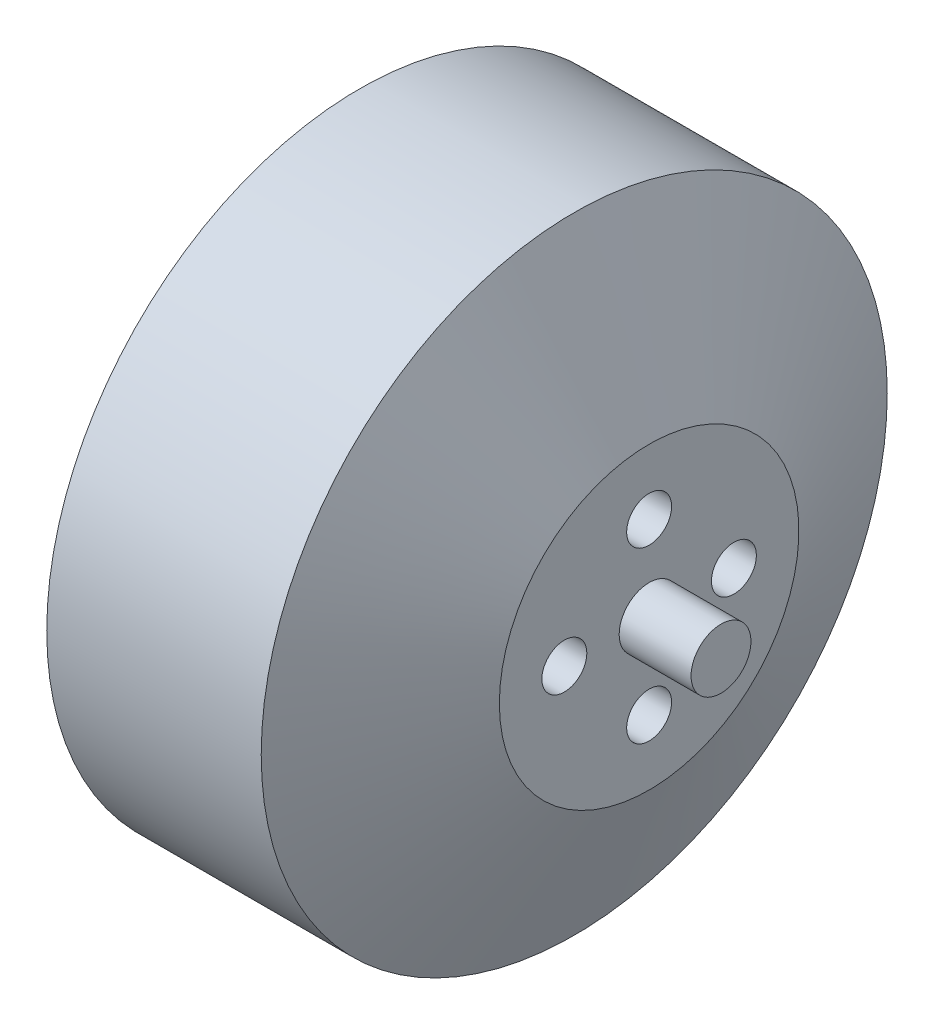
SolidWorks part; units mm, degrees
ref_plane "Plan de face" through (0, 0, 0) normal (0, 0, 1) x (1, 0, 0)
ref_plane "Plan de dessus" through (0, 0, 0) normal (0, 1, 0) x (1, 0, 0)
ref_plane "Plan de droite" through (0, 0, 0) normal (1, 0, 0) x (0, 0, -1)
sketch "Esquisse1" plane through (0, 0, 0) normal (0, 0, 1) x (1, 0, 0)
  line L0 (0, 0) -> (31.3198, 0) construction
  line L1 (0, 20.9) -> (14.32, 20.9)
  line L2 (14.32, 20.9) -> (19.32, 10)
  line L3 (19.32, 10) -> (19.32, 2)
  line L4 (19.32, 2) -> (24.12, 2)
  line L5 (24.12, 2) -> (24.12, 0)
  line L6 (24.12, 0) -> (0, 0)
  line L7 (0, 0) -> (0, 20.9)
  dimension "D1" = 2
  dimension "D2" = 10
  dimension "D3" = 14.32
  dimension "D4" = 5
  dimension "D5" = 20.9
  dimension "D6" = 4.8
revolve "Révolution1" add sketch "Esquisse1" angle 360 about L0
sketch "Esquisse2" plane through (19.32, 0, 0) normal (1, 0, 0) x (0, 0, -1)
  line L0 (-5.66, 0) -> (5.66, 0) construction
  line L1 (0, 0) -> (5.421, 5.421) construction
  line L2 (0, -5.66) -> (0, 5.66) construction
  circle A0 centre (0, -5.66) radius 1.5
  circle A1 centre (-5.66, 0) radius 1.5
  circle A2 centre (0, 5.66) radius 1.5
  circle A3 centre (5.66, 0) radius 1.5
  circle A4 centre (0, 0) radius 10 construction
  dimension "D1" = 3
  dimension "D2" = 3
  dimension "D3" = 20
  dimension "D4" = 11.32
  dimension "D5" = 45
extrude "Enlèv. mat.-Extru.1" cut sketch "Esquisse2" against normal blind 7.5
sketch "Esquisse3" plane through (0, 0, 0) normal (-1, 0, 0) x (0, 0, 1)
  circle A0 centre (0, 0) radius 19.4
  circle A1 centre (0, 0) radius 20.9 construction
  dimension "D1" = 1.5
extrude "Enlèv. mat.-Extru.2" cut sketch "Esquisse3" against normal blind 14.5
